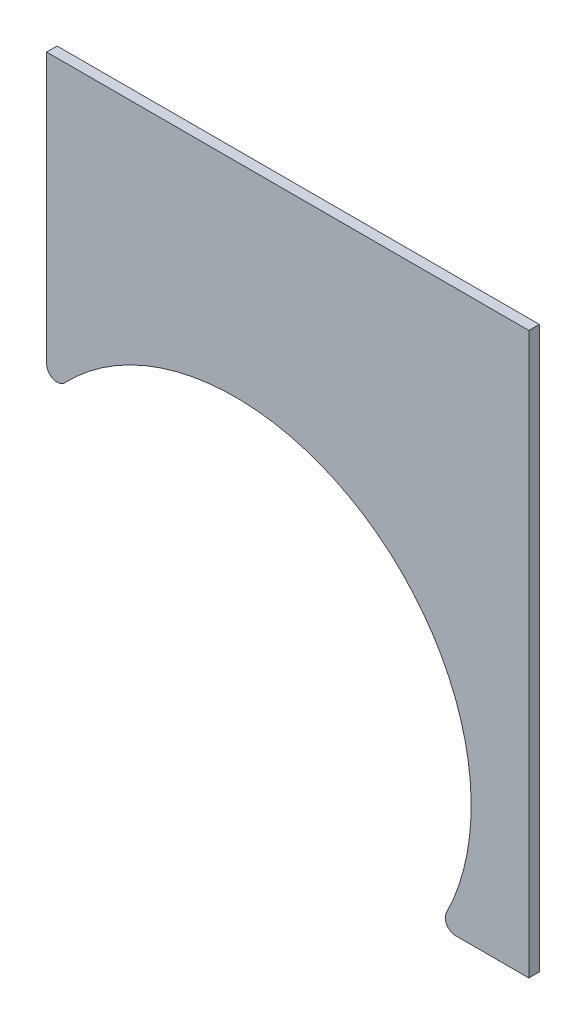
SolidWorks part; units mm, degrees
ref_plane "Plan de face" through (0, 0, 0) normal (0, 0, 1) x (1, 0, 0)
ref_plane "Plan de dessus" through (0, 0, 0) normal (0, 1, 0) x (1, 0, 0)
ref_plane "Plan de droite" through (0, 0, 0) normal (1, 0, 0) x (0, 0, -1)
sketch "Esquisse1" plane through (0, 0, 0) normal (0, 0, 1) x (1, 0, 0)
  line L1 (-36, 84) -> (56, 84)
  line L2 (-36, 84) -> (-36, 27)
  line L3 (38.6782, -23) -> (56, -23)
  line L4 (56, 84) -> (56, -23)
  arc A0 (38.6782, -23) -> (-36, 27) centre (0, 0) ccw
  dimension "D3" = 90
  dimension "D1" = 107
  dimension "D2" = 92
  dimension "D4" = 56
  dimension "D5" = 23
extrude "Boss.-Extru.1" add sketch "Esquisse1" along normal blind 2
fillet "Congé1" radius 2 2 edges at (38.6782, -23, 1) (-36, 27, 1)
